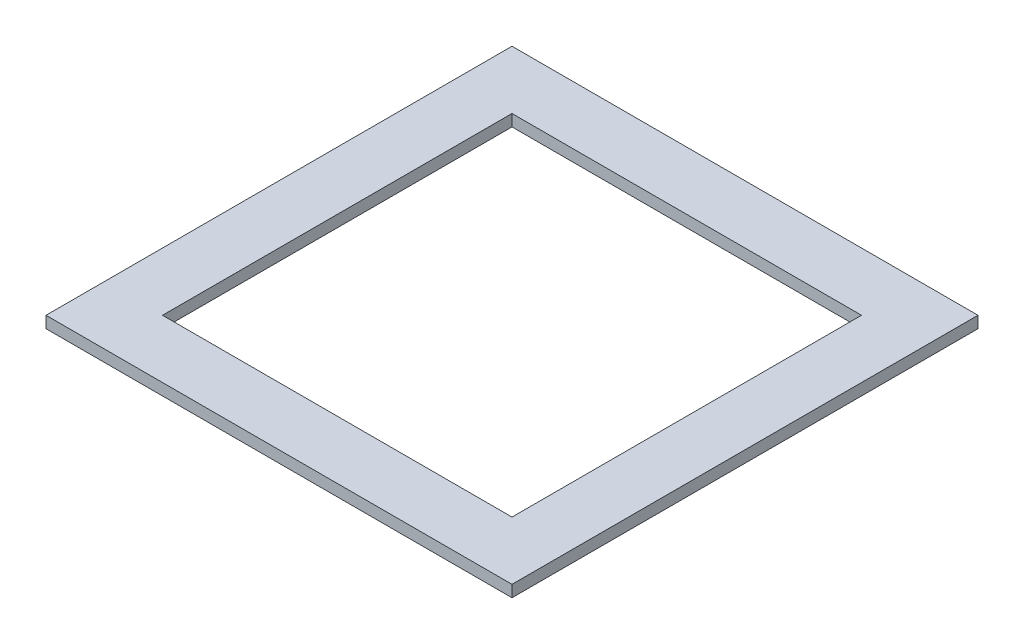
SolidWorks part; units mm, degrees
ref_plane "Alzado" through (0, 0, 0) normal (0, 0, 1) x (1, 0, 0)
ref_plane "Planta" through (0, 0, 0) normal (0, 1, 0) x (1, 0, 0)
ref_plane "Vista lateral" through (0, 0, 0) normal (1, 0, 0) x (0, 0, -1)
sketch "Croquis1" plane through (0, 0, 0) normal (0, 1, 0) x (1, 0, 0)
  line L0 (7.5, 15) -> (7.5, 17.5) construction
  line L1 (0, 0) -> (15, 0)
  line L2 (0, 0) -> (0, 15)
  line L3 (0, 15) -> (15, 15)
  line L4 (15, 0) -> (15, 15)
  line L5 (-2.5, -2.5) -> (17.5, -2.5)
  line L6 (-2.5, -2.5) -> (-2.5, 17.5)
  line L7 (-2.5, 17.5) -> (17.5, 17.5)
  line L8 (17.5, -2.5) -> (17.5, 17.5)
  line L9 (15, 7.5) -> (17.5, 7.5) construction
  dimension "D1" = 15
  dimension "D2" = 20
extrude "Saliente-Extruir1" add sketch "Croquis1" along normal blind 0.5
